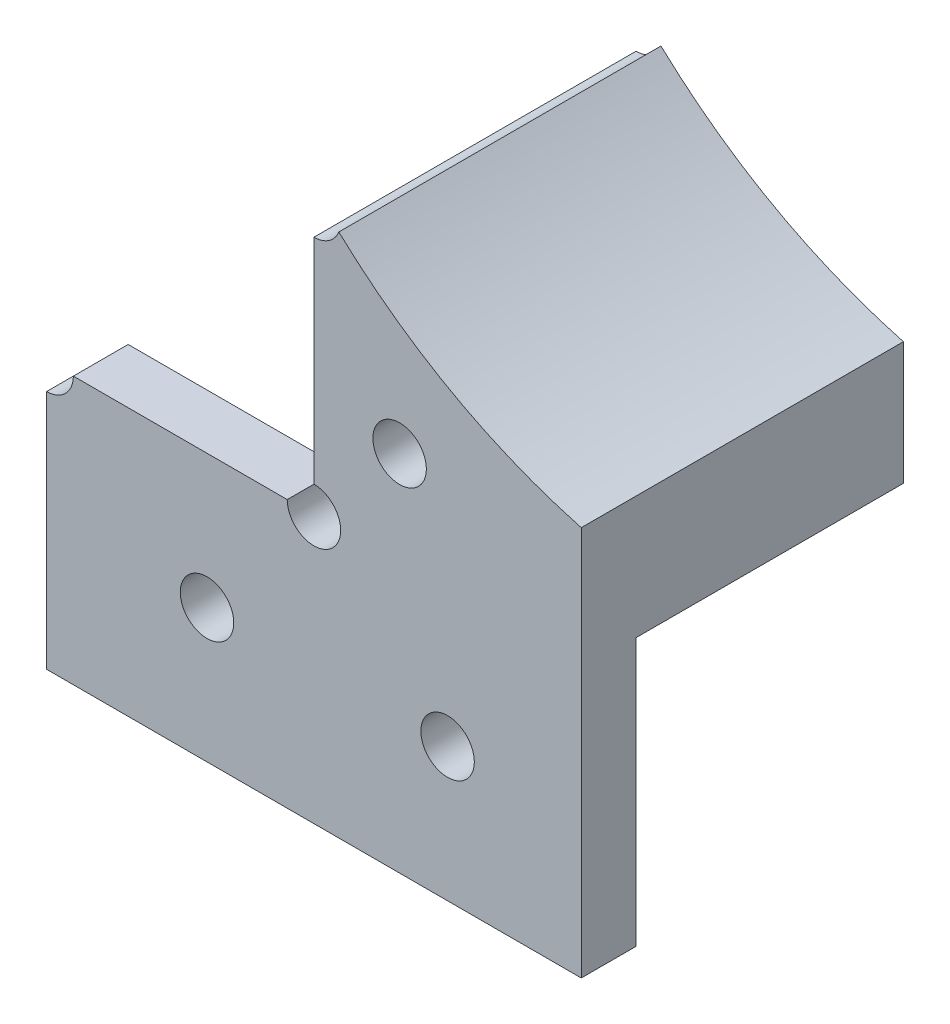
SolidWorks part; units mm, degrees
ref_plane "前视基准面" through (0, 0, 0) normal (0, 0, 1) x (1, 0, 0)
ref_plane "上视基准面" through (0, 0, 0) normal (0, 1, 0) x (1, 0, 0)
ref_plane "右视基准面" through (0, 0, 0) normal (1, 0, 0) x (0, 0, -1)
sketch "草图1" plane through (0, 0, 0) normal (0, 0, 1) x (1, 0, 0)
  line L5 (10, -10) -> (-30, -10)
  line L6 (10, -10) -> (10, 10)
  line L11 (10, 10) -> (-30, 10)
  line L12 (-30, -10) -> (-30, 10)
  circle A1 centre (0, 0) radius 2
  dimension "D3" = 10
  dimension "D5" = 4
  dimension "D1" = 20
  dimension "D2" = 40
  dimension "D4" = 10
extrude "凸台-拉伸1" add sketch "草图1" along normal blind 4.1
sketch "草图2" plane through (0, 0, 4.1) normal (0, 0, 1) x (1, 0, 0)
  line L0 (10, -10) -> (10, 10) construction
  line L1 (10, 10) -> (-10, 10)
  line L2 (10, 10) -> (10, 30)
  line L3 (10, 30) -> (-10, 30)
  line L4 (-10, 10) -> (-10, 30)
  line L5 (10, 10) -> (-30, 10) construction
  dimension "D1" = 20
  dimension "D2" = 20
extrude "凸台-拉伸2" add sketch "草图2" against normal blind 24.1
sketch "草图3" plane through (0, 0, 4.1) normal (0, 0, 1) x (1, 0, 0)
  line L0 (-11.9525, 30.4331) -> (-10, 28)
  line L4 (-10, 30) -> (-10, 10) construction
  line L5 (-10, 10) -> (-30, 10) construction
  line L6 (10, -10) -> (10, 30)
  line L7 (10, 30) -> (-10, 30)
  line L8 (-10, 30) -> (-10, 10)
  line L9 (-10, 10) -> (-30, 10)
  line L10 (-30, 10) -> (-30, -10)
  line L11 (-30, -10) -> (10, -10)
  line L12 (10, 19.1784) -> (10, 30)
  line L13 (10, 30) -> (-8, 30)
  line L18 (-12, 10) -> (-10, 12)
  line L19 (10, 30) -> (-10, 30) construction
  arc A0 (-8, 30) -> (-11.9525, 30.4331) centre (-10, 30) ccw
  circle A1 centre (-18, 0) radius 2
  circle A2 centre (-30, 10) radius 2
  arc A3 (-8.1387, 29.2683) -> (10, 19.1784) centre (21.2157, 60.6899) ccw
  arc A5 (-12, 10) -> (-10, 12) centre (-10, 10) ccw
  arc A6 (-10, 28) -> (-8.1387, 29.2683) centre (-10, 30) ccw
  circle A8 centre (-3.5892, 17.1784) radius 2
  dimension "D2" = 4
  dimension "D3" = 2
  dimension "D5" = 2
  dimension "D6" = 4
  dimension "D4" = 8
  dimension "D1" = 0
extrude "切除-拉伸1" cut sketch "草图3" against normal through all
